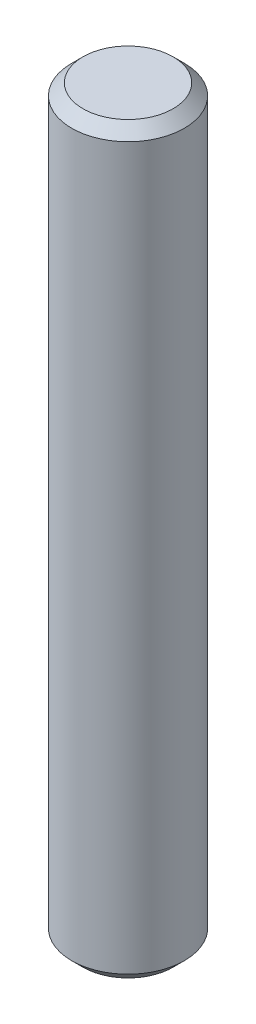
SolidWorks part; units mm, degrees
material "AISI 316 Annealed Stainless Steel Bar (SS)"
ref_plane "Front Plane" through (0, 0, 0) normal (0, 0, 1) x (1, 0, 0)
ref_plane "Top Plane" through (0, 0, 0) normal (0, 1, 0) x (1, 0, 0)
ref_plane "Right Plane" through (0, 0, 0) normal (1, 0, 0) x (0, 0, -1)
sketch "Sketch1" plane through (0, 0, 0) normal (0, 1, 0) x (1, 0, 0)
  circle A0 centre (0, 0) radius 3.175
  dimension "D1" = 6.35
extrude "Boss-Extrude1" add sketch "Sketch1" along normal blind 41.91
chamfer "Chamfer1" distance 0.635 angle 45 2 edges at (0, 0, 3.175) (0, 41.91, 3.175)
